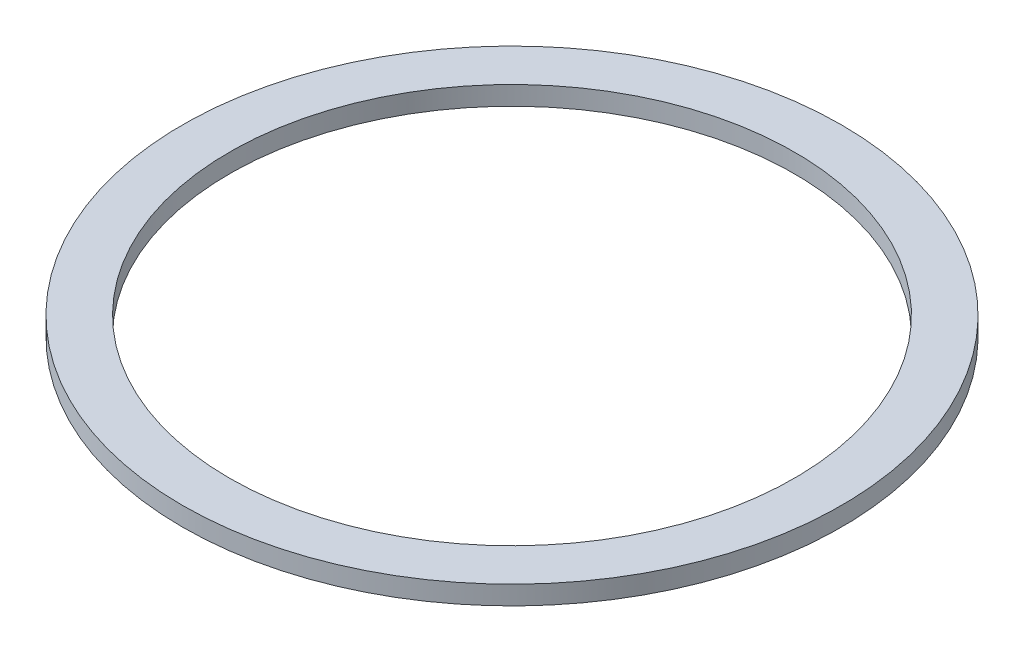
SolidWorks part; units mm, degrees
ref_plane "前视基准面" through (0, 0, 0) normal (0, 0, 1) x (1, 0, 0)
ref_plane "上视基准面" through (0, 0, 0) normal (0, 1, 0) x (1, 0, 0)
ref_plane "右视基准面" through (0, 0, 0) normal (1, 0, 0) x (0, 0, -1)
other "Configuration Table"
sketch "草图1" plane through (0, 0, 0) normal (0, 1, 0) x (1, 0, 0)
  circle A0 centre (0, 0) radius 15
  circle A1 centre (0, 0) radius 17.5
  dimension "D1" = 35
  dimension "D2" = 30
extrude "凸台-拉伸1" add sketch "草图1" along normal blind 1
